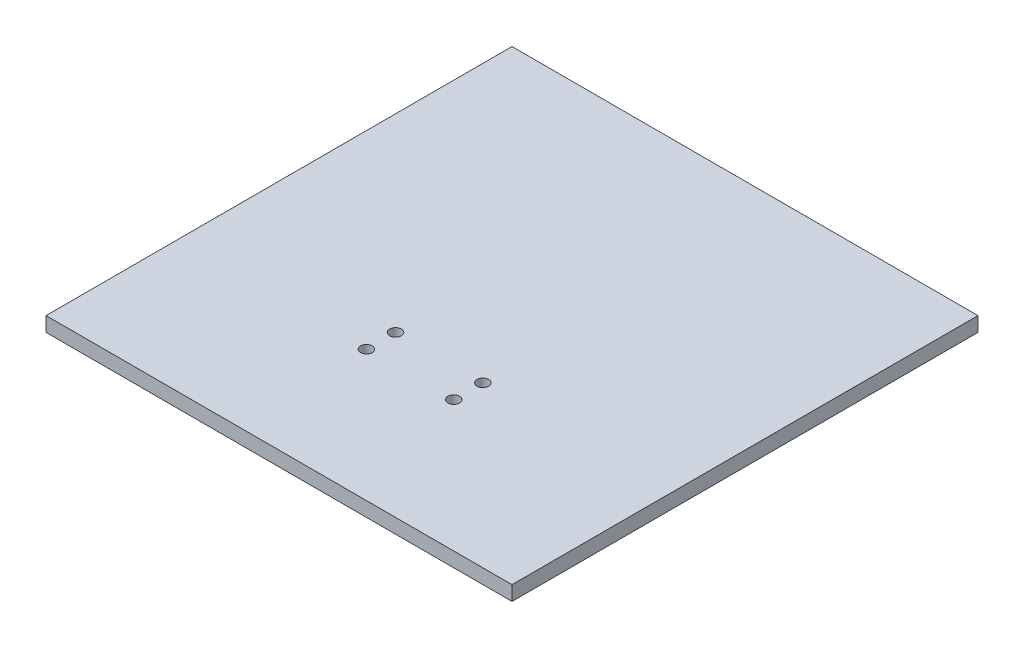
SolidWorks part; units mm, degrees
ref_plane "Front Plane" through (0, 0, 0) normal (0, 0, 1) x (1, 0, 0)
ref_plane "Top Plane" through (0, 0, 0) normal (0, 1, 0) x (1, 0, 0)
ref_plane "Right Plane" through (0, 0, 0) normal (1, 0, 0) x (0, 0, -1)
sketch "Sketch2" plane through (0, 0, 0) normal (0, 1, 0) x (1, 0, 0)
  line L1 (0, 0) -> (203.2, 0)
  line L2 (0, 0) -> (0, 203.2)
  line L3 (0, 203.2) -> (203.2, 203.2)
  line L4 (203.2, 0) -> (203.2, 203.2)
  dimension "D1" = 203.2
  dimension "D2" = 203.2
extrude "Boss-Extrude2" add sketch "Sketch2" along normal blind 6.35
hole_wizard "CSK for #10 Flat Head Machine Screw (100)1" positions "Sketch5" profile "Sketch4" countersink size "#10" standard "ANSI Inch" end condition through all
sketch "Sketch5" plane through (0, 0, 0) normal (0, -1, 0) x (-1, 0, 0)
  line L1 (-76.2, 76.2) -> (-127, 76.2) construction
  line L2 (-76.2, 76.2) -> (-76.2, 50.8) construction
  line L3 (-76.2, 50.8) -> (-127, 50.8) construction
  line L4 (-127, 76.2) -> (-127, 50.8) construction
  line L5 (-101.6, 50.8) -> (-101.6, 101.6) construction
  line L7 (-76.2, 63.5) -> (-127, 63.5) construction
  line L9 (0, 0) -> (-203.2, 203.2) construction
  point P0 (-82.55, 57.15)
  point P163 (-101.6, 101.6)
  point P165 (-82.55, 69.85)
  point P167 (-120.65, 57.15)
  point P168 (-120.65, 69.85)
  dimension "D1" = 50.8
  dimension "D2" = 25.4
  dimension "D3" = 25.4
  dimension "D4" = 6.35
  dimension "D5" = 6.35
sketch "Sketch4" plane through (82.55, 0, -57.15) normal (1, 0, 0) x (0, 0, -1)
  line L0 (0, 0) -> (0, 6.35)
  line L1 (0, 6.35) -> (2.5527, 6.35)
  line L2 (2.5527, 6.35) -> (2.5527, 1.9608)
  line L3 (2.5527, 1.9608) -> (4.8895, 0)
  line L5 (4.8895, 0) -> (0, 0)
  line L6 (-2.5527, 1.9608) -> (-4.8895, 0) construction
  line L11 (0, -6.35) -> (0, 107.95) construction
  dimension "Thru Hole Dia." = 5.1054
  dimension "Thru Hole Depth" = 6.35
  dimension "Near C'Sink Dia." = 9.779
  dimension "Near C'Sink Angle" = 100
